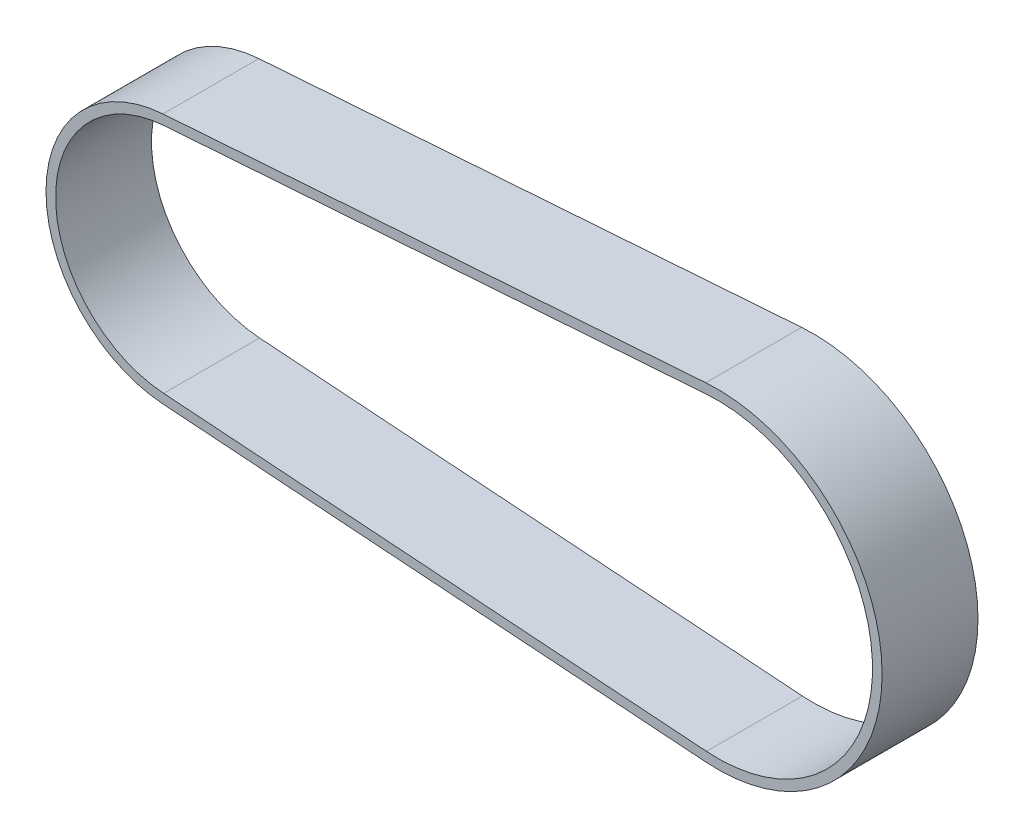
SolidWorks part; units mm, degrees
material "Caoutchouc"
ref_plane "Front" through (0, 0, 0) normal (0, 0, 1) x (1, 0, 0)
ref_plane "Top" through (0, 0, 0) normal (0, 1, 0) x (1, 0, 0)
ref_plane "Right" through (0, 0, 0) normal (1, 0, 0) x (0, 0, -1)
sketch "Esquisse1" plane through (0, 0, 0) normal (0, 0, 1) x (1, 0, 0)
  line L0 (-0.8613, 12.0994) -> (55.7454, 16.1292)
  line L1 (55.7454, -16.1292) -> (-0.8613, -12.0994)
  arc A0 (55.7454, 16.1292) -> (55.7454, -16.1292) centre (56.8936, 0) cw
  arc A1 (-0.8613, -12.0994) -> (-0.8613, 12.0994) centre (0, 0) cw
  point P5 (0, 0)
  point P9 (0, 0)
  dimension "D1" = 12.13
  dimension "D2" = 16.17
  dimension "D3" = 56.75
extrude "Extru.-Mince1" add sketch "Esquisse1" along normal mid plane 10 thin thin type one direction wall 1
